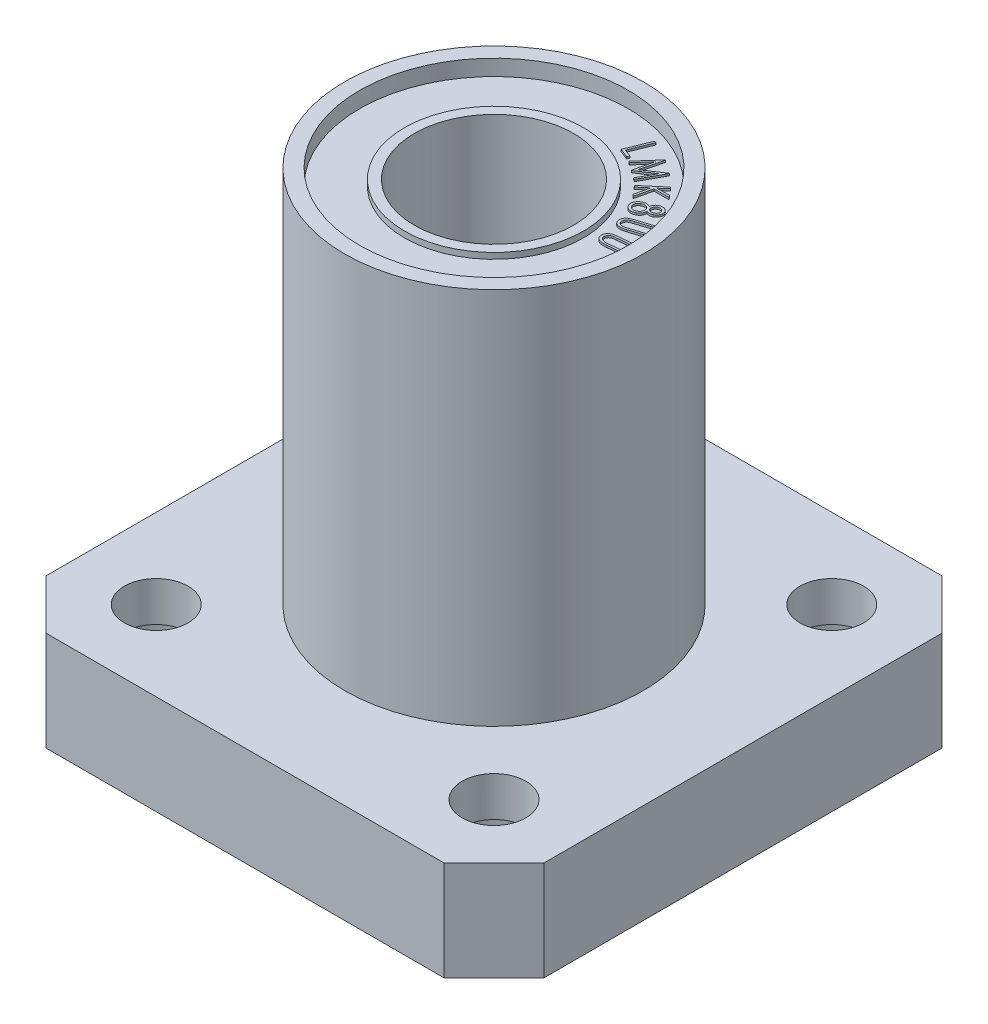
SolidWorks part; units mm, degrees
material "ABS"
ref_plane "Front Plane" through (0, 0, 0) normal (0, 0, 1) x (1, 0, 0)
ref_plane "Top Plane" through (0, 0, 0) normal (0, 1, 0) x (1, 0, 0)
ref_plane "Right Plane" through (0, 0, 0) normal (1, 0, 0) x (0, 0, -1)
sketch "Sketch1" plane through (0, 0, 0) normal (0, 1, 0) x (1, 0, 0)
  line L0 (-12.5, 10) -> (-10, 12.5)
  line L1 (-10, -12.5) -> (10, -12.5)
  line L2 (-12.5, -10) -> (-12.5, 10)
  line L3 (-10, 12.5) -> (10, 12.5)
  line L4 (12.5, -10) -> (12.5, 10)
  line L5 (-12.5, -12.5) -> (12.5, 12.5) construction
  line L6 (-12.5, 12.5) -> (12.5, -12.5) construction
  line L7 (10, 12.5) -> (12.5, 10)
  line L8 (10, -12.5) -> (12.5, -10)
  line L9 (-12.5, -10) -> (-10, -12.5)
  circle A0 centre (0, 0) radius 7.5
  point P0 (0, 0)
  dimension "D3" = 15
  dimension "D1" = 25
  dimension "D2" = 20
extrude "Boss-Extrude1" add sketch "Sketch1" along normal blind 5 contours L2 L0 L3 L7 L4 L8 L1 L9 | A0
sketch "Sketch2" plane through (0, 0, 0) normal (0, -1, 0) x (1, 0, 0)
  line L1 (-8.4853, -8.4853) -> (8.4853, -8.4853) construction
  line L2 (-8.4853, -8.4853) -> (-8.4853, 8.4853) construction
  line L3 (-8.4853, 8.4853) -> (8.4853, 8.4853) construction
  line L4 (8.4853, -8.4853) -> (8.4853, 8.4853) construction
  line L5 (-8.4853, -8.4853) -> (8.4853, 8.4853) construction
  line L6 (-8.4853, 8.4853) -> (8.4853, -8.4853) construction
  circle A0 centre (-8.4853, 8.4853) radius 3
  circle A1 centre (8.4853, 8.4853) radius 3
  circle A2 centre (8.4853, -8.4853) radius 3
  circle A3 centre (-8.4853, -8.4853) radius 3
  point P0 (0, 0)
  dimension "D2" = 6
  dimension "D1" = 12
extrude "Cut-Extrude1" cut sketch "Sketch2" against normal blind 3
sketch "Sketch3" plane through (0, 3, 0) normal (0, -1, 0) x (1, 0, 0)
  line L1 (8.4853, -8.4853) -> (-8.4853, -8.4853) construction
  line L2 (8.4853, -8.4853) -> (8.4853, 8.4853) construction
  line L3 (8.4853, 8.4853) -> (-8.4853, 8.4853) construction
  line L4 (-8.4853, -8.4853) -> (-8.4853, 8.4853) construction
  line L5 (8.4853, -8.4853) -> (-8.4853, 8.4853) construction
  line L6 (8.4853, 8.4853) -> (-8.4853, -8.4853) construction
  circle A0 centre (-8.4853, 8.4853) radius 1.6
  circle A1 centre (8.4853, 8.4853) radius 1.6
  circle A2 centre (8.4853, -8.4853) radius 1.6
  circle A3 centre (-8.4853, -8.4853) radius 1.6
  point P3 (0, 0)
  dimension "D1" = 3.2
extrude "Cut-Extrude2" cut sketch "Sketch3" against normal up to next
sketch "Sketch5" plane through (0, 0, 0) normal (0, 0, 1) x (1, 0, 0)
  line L0 (4, 23.5) -> (4, 0.5)
  line L1 (4, 0.5) -> (4.5, 0.5)
  line L2 (4.5, 0.5) -> (4.5, 0.8)
  line L3 (4.5, 0.8) -> (6.75, 0.8)
  line L4 (6.75, 0.8) -> (6.75, 0)
  line L6 (6.75, 0) -> (7.5, 0)
  line L7 (7.5, 0) -> (7.5, 24)
  line L8 (7.5, 24) -> (6.75, 24)
  line L9 (6.75, 24) -> (6.75, 23.2)
  line L10 (6.75, 23.2) -> (4.5, 23.2)
  line L11 (4.5, 23.2) -> (4.5, 23.5)
  line L12 (4.5, 23.5) -> (4, 23.5)
  line L13 (-10, 0) -> (10, 0) construction
  dimension "D1" = 4
  dimension "D2" = 0.3
  dimension "D3" = 0.8
  dimension "D4" = 6.75
  dimension "D5" = 0.5
  dimension "D6" = 7.5
  dimension "D7" = 24
  dimension "D8" = 6.75
  dimension "D9" = 0.3
  dimension "D10" = 0.8
  dimension "D11" = 0.5
ref_axis "Axis1" through (0, 25.2, 0) along (0, -1, 0)
revolve "Revolve1" add sketch "Sketch5" angle 360 about axis through (0, 25.2, 0) along (0, -1, 0)
sketch "Sketch7" plane through (0, 0.8, 0) normal (0, -1, 0) x (-1, 0, 0)
  circle A0 centre (0, 0) radius 5 construction
  text T0 "LMK8UU" font "Century Gothic" height 1.3
  dimension "D1" = 10
extrude "Boss-Extrude2" add sketch "Sketch7" along normal blind 0.1
sketch "Sketch8" plane through (0, 23.2, 0) normal (0, 1, 0) x (1, 0, 0)
  circle A0 centre (0, 0) radius 5 construction
  text T0 "LMK8UU" font "Century Gothic" height 1.3
  dimension "D1" = 10
extrude "Boss-Extrude3" add sketch "Sketch8" along normal blind 0.1
